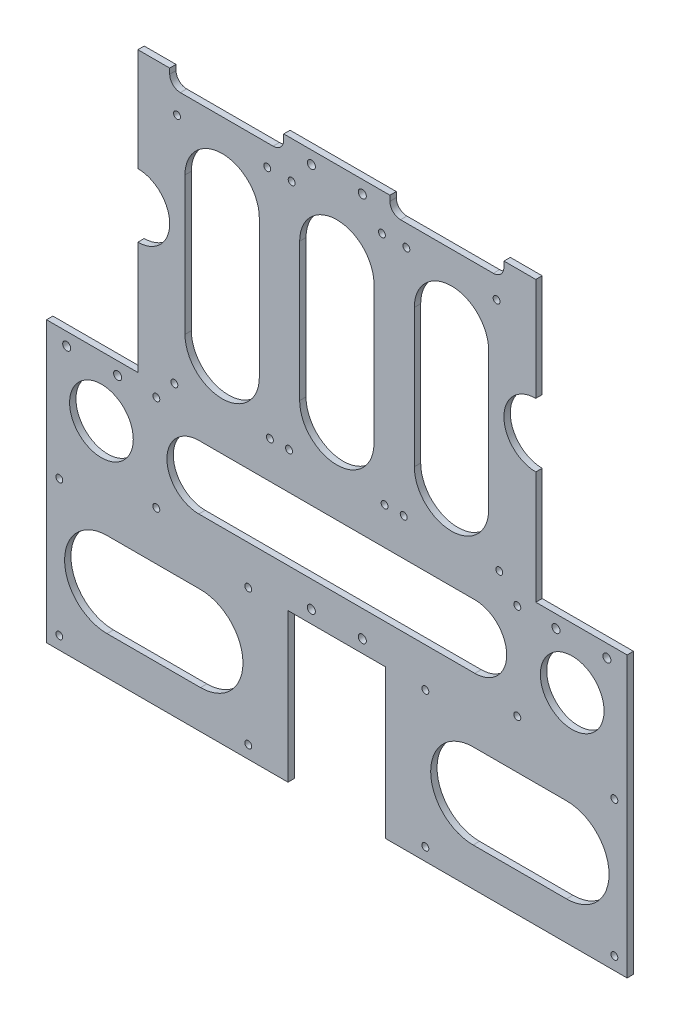
SolidWorks part; units mm, degrees
material "Oak"
ref_plane "Front Plane" through (0, 0, 0) normal (0, 0, 1) x (1, 0, 0)
ref_plane "Top Plane" through (0, 0, 0) normal (0, 1, 0) x (1, 0, 0)
ref_plane "Right Plane" through (0, 0, 0) normal (1, 0, 0) x (0, 0, -1)
sketch "Sketch1" plane through (0, 0, 0) normal (0, 0, 1) x (1, 0, 0)
  line L1 (0, 0) -> (273.4, 0)
  line L2 (0, 0) -> (0, -263.4)
  line L3 (0, -263.4) -> (273.4, -263.4)
  line L4 (273.4, 0) -> (273.4, -263.4)
  dimension "D1" = 273.4
  dimension "D2" = 263.4
extrude "Boss-Extrude1" add sketch "Sketch1" along normal blind 3
sketch "Sketch2" plane through (0, 0, 3) normal (0, 0, 1) x (1, 0, 0)
  line L1 (0, 0) -> (43, 0)
  line L2 (0, 0) -> (0, -131.64)
  line L3 (0, -131.64) -> (43, -131.64)
  line L4 (43, 0) -> (43, -131.64)
  line L9 (273.4, 0) -> (230.4, 0)
  line L10 (273.4, 0) -> (273.4, -131.64)
  line L11 (273.4, -131.64) -> (230.4, -131.64)
  line L12 (230.4, 0) -> (230.4, -131.64)
  dimension "D1" = 43
  dimension "D2" = 131.64
  dimension "D5" = 43
  dimension "D6" = 131.64
extrude "Cut-Extrude1" cut sketch "Sketch2" against normal through all
sketch "Sketch3" plane through (0, 0, 0) normal (0, 0, -1) x (-1, 0, 0)
  line L0 (0, -263.4) -> (-273.4, -263.4) construction
  line L1 (-159.7, -193.4) -> (-113.7, -193.4)
  line L2 (-159.7, -193.4) -> (-159.7, -263.4)
  line L3 (-159.7, -263.4) -> (-113.7, -263.4)
  line L4 (-113.7, -193.4) -> (-113.7, -263.4)
  line L5 (-273.4, -263.4) -> (-273.4, -131.64) construction
  dimension "D1" = 46
  dimension "D2" = 70
  dimension "D3" = 113.7
extrude "Cut-Extrude2" cut sketch "Sketch3" against normal through all
hole_wizard "#4 Clearance Hole1" positions "Sketch5" profile "Sketch6" hole size "#4" standard "ANSI Inch" end condition up to next
sketch "Sketch5" plane through (0, 0, 0) normal (0, 0, -1) x (-1, 0, 0)
  line L4 (-159.7, -263.4) -> (-273.4, -263.4) construction
  line L8 (-221.7, -137.5) -> (-51.7, -137.5) construction
  line L9 (-221.7, -137.5) -> (-221.7, -182.5) construction
  line L10 (-221.7, -182.5) -> (-51.7, -182.5) construction
  line L11 (-51.7, -137.5) -> (-51.7, -182.5) construction
  line L31 (-157.95, -17.5) -> (-115.45, -17.5) construction
  line L32 (-159.2, -127.5) -> (-114.2, -127.5) construction
  line L35 (-136.7, 0) -> (-136.7, -193.4) construction
  line L36 (-230.4, 0) -> (-43, 0) construction
  line L37 (-113.7, -193.4) -> (-159.7, -193.4) construction
  line L38 (-103.95, -17.5) -> (-61.45, -17.5) construction
  line L39 (-105.2, -127.5) -> (-60.2, -127.5) construction
  line L40 (-211.95, -17.5) -> (-169.45, -17.5) construction
  line L41 (-213.2, -127.5) -> (-168.2, -127.5) construction
  line L42 (0, -131.64) -> (0, -263.4) construction
  line L43 (-273.4, -263.4) -> (-273.4, -131.64) construction
  point P0 (-267.4, -257.4)
  point P2 (-267.4, -193.4)
  point P4 (-178.4, -193.4)
  point P6 (-178.4, -257.4)
  point P8 (-95, -257.4)
  point P10 (-95, -193.4)
  point P12 (-6, -193.4)
  point P14 (-6, -257.4)
  point P16 (-221.7, -137.5)
  point P18 (-221.7, -182.5)
  point P20 (-51.7, -137.5)
  point P22 (-51.7, -182.5)
  point P276 (-115.45, -17.5)
  point P277 (-157.95, -17.5)
  point P278 (-114.2, -127.5)
  point P279 (-159.2, -127.5)
  point P302 (-136.7, -17.5)
  point P306 (-136.7, -127.5)
  point P311 (-61.45, -17.5)
  point P312 (-103.95, -17.5)
  point P313 (-60.2, -127.5)
  point P314 (-105.2, -127.5)
  point P320 (-169.45, -17.5)
  point P321 (-211.95, -17.5)
  point P322 (-168.2, -127.5)
  point P323 (-213.2, -127.5)
  point P329 (0, 0)
  point P330 (-136.7, -137.5)
  dimension "D1" = 89
  dimension "D2" = 6
  dimension "D3" = 64
  dimension "D4" = 6
  dimension "D5" = 89
  dimension "D6" = 64
  dimension "D7" = 6
  dimension "D8" = 45
  dimension "D9" = 170
  dimension "D10" = 42.5
  dimension "D11" = 45
  dimension "D12" = 110
  dimension "D13" = 17.5
  dimension "D14" = 2
  dimension "D15" = 10
sketch "Sketch6" plane through (267.4, -257.4, 0) normal (1, 0, 0) x (0, 1, 0)
  line L0 (0, 0) -> (0, 3)
  line L1 (0, 3) -> (1.6319, 3)
  line L2 (1.6319, 3) -> (1.632, 0)
  line L5 (1.632, 0) -> (0, 0)
  line L11 (0, -6.35) -> (0, 107.95) construction
  dimension "Thru Hole Dia." = 3.2639
  dimension "Thru Hole Depth" = 3
sketch "Sketch4" plane through (0, 0, 3) normal (0, 0, 1) x (1, 0, 0)
  line L0 (230.4, 0) -> (43, 0) construction
  line L1 (58, 0) -> (111.7, 0)
  line L2 (58, 0) -> (58, -2.5)
  line L3 (63, -7.5) -> (106.7, -7.5)
  line L4 (111.7, 0) -> (111.7, -2.5)
  line L6 (43, -131.64) -> (43, 0) construction
  line L7 (136.7, 0) -> (136.7, -193.4) construction
  line L8 (113.7, -193.4) -> (159.7, -193.4) construction
  line L13 (0, -131.64) -> (0, -263.4) construction
  line L15 (43, -48.5) -> (43, -78.5)
  line L16 (230.4, -48.5) -> (230.4, -78.5)
  line L17 (210.4, -7.5) -> (166.7, -7.5)
  line L18 (161.7, 0) -> (161.7, -2.5)
  line L19 (215.4, 0) -> (161.7, 0)
  line L20 (215.4, 0) -> (215.4, -2.5)
  line L21 (51.7, -137.5) -> (51.7, -182.5) construction
  line L22 (51.7, -160) -> (0, -160) construction
  arc A0 (43, -48.5) -> (43, -78.5) centre (43, -63.5) cw
  circle A1 centre (25.85, -160) radius 15
  circle A2 centre (247.55, -160) radius 15
  arc A3 (230.4, -48.5) -> (230.4, -78.5) centre (230.4, -63.5) ccw
  arc A4 (58, -2.5) -> (63, -7.5) centre (63, -2.5) ccw
  arc A5 (106.7, -7.5) -> (111.7, -2.5) centre (106.7, -2.5) ccw
  arc A6 (166.7, -7.5) -> (161.7, -2.5) centre (166.7, -2.5) cw
  arc A7 (210.4, -7.5) -> (215.4, -2.5) centre (210.4, -2.5) ccw
  point P21 (0, 0)
  point P22 (0, 0)
  point P36 (0, 0)
  point P39 (58, -7.5)
  point P42 (111.7, -7.5)
  point P45 (161.7, -7.5)
  point P48 (215.4, -7.5)
  dimension "D4" = 5
  dimension "D7" = 15
  dimension "D8" = 30
  dimension "D1" = 7.5
  dimension "D2" = 15
  dimension "D3" = 25
  dimension "D6" = 63.5
extrude "Cut-Extrude3" cut sketch "Sketch4" against normal up to next
hole_wizard "#6 Clearance Hole1" positions "Sketch7" profile "Sketch8" hole size "#6" standard "ANSI Inch" end condition up to next
sketch "Sketch7" plane through (0, 0, 3) normal (0, 0, 1) x (1, 0, 0)
  line L1 (111.7, -2.5) -> (111.7, 0) construction
  line L4 (113.7, -263.4) -> (113.7, -193.4) construction
  line L5 (0, -131.64) -> (43, -131.64) construction
  line L6 (113.7, -193.4) -> (159.7, -193.4) construction
  line L7 (230.4, -131.64) -> (273.4, -131.64) construction
  line L8 (161.7, 0) -> (111.7, 0) construction
  line L9 (0, -131.64) -> (0, -263.4) construction
  line L10 (273.4, -263.4) -> (273.4, -131.64) construction
  point P0 (124.7, -6)
  point P2 (148.7, -6)
  point P4 (9.5, -137.64)
  point P6 (33.5, -137.64)
  point P8 (124.7, -187.4)
  point P10 (148.7, -187.4)
  point P20 (263.9, -137.64)
  point P22 (239.9, -137.64)
  dimension "D1" = 24
  dimension "D2" = 24
  dimension "D3" = 24
  dimension "D4" = 24
  dimension "D5" = 13
  dimension "D6" = 11
  dimension "D7" = 6
  dimension "D8" = 6
  dimension "D9" = 6
  dimension "D10" = 6
  dimension "D11" = 9.5
  dimension "D12" = 9.5
sketch "Sketch8" plane through (124.7, -6, 3) normal (1, 0, 0) x (0, -1, 0)
  line L0 (0, 0) -> (0, 3)
  line L1 (0, 3) -> (1.8986, 3)
  line L2 (1.8986, 3) -> (1.8986, 0)
  line L5 (1.8986, 0) -> (0, 0)
  line L11 (0, -6.35) -> (0, 107.95) construction
  dimension "Thru Hole Dia." = 3.7973
  dimension "Thru Hole Depth" = 3
sketch "Sketch9" plane through (0, 0, 3) normal (0, 0, 1) x (1, 0, 0)
  line L0 (72.5, -225.4) -> (28.5, -225.4) construction
  line L1 (72.5, -245.4) -> (28.5, -245.4)
  line L2 (72.5, -205.4) -> (28.5, -205.4)
  line L3 (200.9, -225.4) -> (244.9, -225.4) construction
  line L6 (71.7, -160) -> (201.7, -160) construction
  line L7 (71.7, -145) -> (201.7, -145)
  line L8 (71.7, -175) -> (201.7, -175)
  line L9 (190.7, -40) -> (190.7, -105) construction
  line L12 (136.7, -40) -> (136.7, -105) construction
  line L13 (154.2, -40) -> (154.2, -105)
  line L14 (119.2, -40) -> (119.2, -105)
  line L15 (208.2, -40) -> (208.2, -105)
  line L18 (136.7, 0) -> (136.7, -193.4) construction
  line L19 (161.7, 0) -> (111.7, 0) construction
  line L20 (113.7, -193.4) -> (159.7, -193.4) construction
  line L21 (115.45, -17.5) -> (114.2, -127.5) construction
  line L22 (51.8, -160) -> (221.7, -160) construction
  line L23 (114.2, -127.5) -> (159.2, -127.5) construction
  line L24 (159.2, -127.5) -> (157.95, -17.5) construction
  line L25 (157.95, -17.5) -> (115.45, -17.5) construction
  line L26 (173.2, -40) -> (173.2, -105)
  line L27 (82.7, -40) -> (82.7, -105) construction
  line L28 (100.2, -40) -> (100.2, -105)
  line L29 (65.2, -40) -> (65.2, -105)
  line L30 (200.9, -245.4) -> (244.9, -245.4)
  line L31 (200.9, -205.4) -> (244.9, -205.4)
  line L32 (6, -193.4) -> (95, -193.4) construction
  line L33 (95, -193.4) -> (95, -257.4) construction
  line L34 (95, -257.4) -> (6, -257.4) construction
  line L35 (6, -257.4) -> (6, -193.4) construction
  line L36 (6, -225.4) -> (95, -225.4) construction
  line L37 (51.7, -137.5) -> (51.7, -182.5) construction
  line L38 (221.7, -137.5) -> (51.7, -137.5) construction
  line L39 (221.7, -137.5) -> (221.7, -182.5) construction
  line L40 (51.7, -160) -> (221.7, -160) construction
  arc A0 (72.5, -245.4) -> (72.5, -205.4) centre (72.5, -225.4) ccw
  arc A1 (28.5, -205.4) -> (28.5, -245.4) centre (28.5, -225.4) ccw
  arc A4 (71.7, -145) -> (71.7, -175) centre (71.7, -160) ccw
  arc A5 (201.7, -175) -> (201.7, -145) centre (201.7, -160) ccw
  arc A8 (154.2, -40) -> (119.2, -40) centre (136.7, -40) ccw
  arc A9 (119.2, -105) -> (154.2, -105) centre (136.7, -105) ccw
  circle A12 centre (25.85, -160) radius 15 construction
  arc A13 (208.2, -40) -> (173.2, -40) centre (190.7, -40) ccw
  arc A14 (200.9, -245.4) -> (200.9, -205.4) centre (200.9, -225.4) cw
  arc A15 (173.2, -105) -> (208.2, -105) centre (190.7, -105) ccw
  arc A16 (244.9, -205.4) -> (244.9, -245.4) centre (244.9, -225.4) cw
  arc A17 (100.2, -40) -> (65.2, -40) centre (82.7, -40) ccw
  arc A18 (65.2, -105) -> (100.2, -105) centre (82.7, -105) ccw
  point P2 (50.5, -225.4)
  point P9 (222.9, -225.4)
  point P14 (136.7, -160)
  point P21 (190.7, -72.5)
  point P28 (136.7, -72.5)
  point P36 (82.7, -72.5)
  point P68 (166.2528, -160)
  point P69 (0, 0)
  point P70 (258.1652, -160)
  point P71 (220.8556, -160)
  dimension "D5" = 22.5
  dimension "D6" = 20
  dimension "D3" = 17.5
  dimension "D4" = 22.5
  dimension "D11" = 20
  dimension "D1" = 22.5
  dimension "D2" = 22.5
  dimension "D7" = 2
  dimension "D9" = 54
  dimension "D10" = 54
  dimension "D8" = 2
extrude "Cut-Extrude4" cut sketch "Sketch9" against normal up to next
